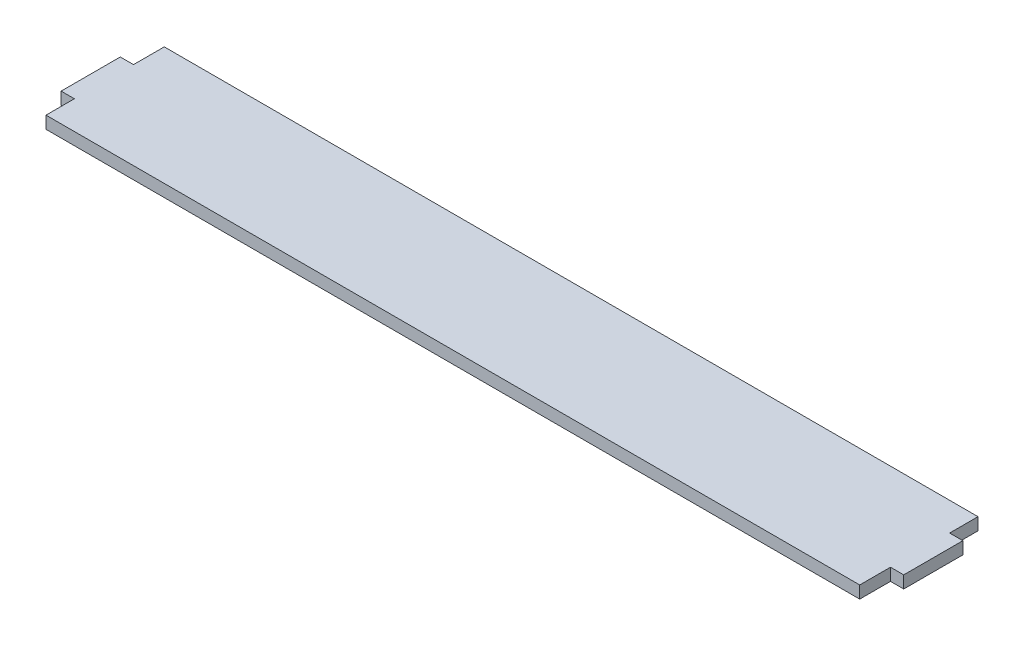
SolidWorks part; units mm, degrees
ref_plane "Front Plane" through (0, 0, 0) normal (0, 0, 1) x (1, 0, 0)
ref_plane "Top Plane" through (0, 0, 0) normal (0, 1, 0) x (1, 0, 0)
ref_plane "Right Plane" through (0, 0, 0) normal (1, 0, 0) x (0, 0, -1)
sketch "Sketch1" plane through (0, 0, 0) normal (0, 1, 0) x (1, 0, 0)
  line L1 (-43, 6.25) -> (43, 6.25)
  line L2 (-43, 6.25) -> (-43, -6.25)
  line L3 (-43, -6.25) -> (43, -6.25)
  line L4 (43, 6.25) -> (43, -6.25)
  line L5 (-43, 6.25) -> (43, -6.25) construction
  line L6 (-43, -6.25) -> (43, 6.25) construction
  point P0 (0, 0)
  dimension "D1" = 86
  dimension "D2" = 12.5
extrude "Boss-Extrude1" add sketch "Sketch1" along normal blind 1.3
sketch "Sketch2" plane through (0, 0, 0) normal (0, 1, 0) x (1, 0, 0)
  line L0 (-43, 6.25) -> (-43, -6.25) construction
  line L1 (-43, 3) -> (-44.4, 3)
  line L2 (-43, 3) -> (-43, -3.25)
  line L3 (-43, -3.25) -> (-44.4, -3.25)
  line L4 (-44.4, 3) -> (-44.4, -3.25)
  line L5 (43, -6.25) -> (43, 6.25) construction
  line L6 (43, 3.25) -> (44.4, 3.25)
  line L7 (43, 3.25) -> (43, -3)
  line L8 (43, -3) -> (44.4, -3)
  line L9 (44.4, 3.25) -> (44.4, -3)
  line L10 (-0.715, 0) -> (0.715, 0) construction
  dimension "D1" = 1.4
  dimension "D2" = 6.25
  dimension "D3" = 3
  dimension "D4" = 1.4
  dimension "D5" = 6.25
  dimension "D6" = 3
extrude "Boss-Extrude2" add sketch "Sketch2" along normal blind 1.3
